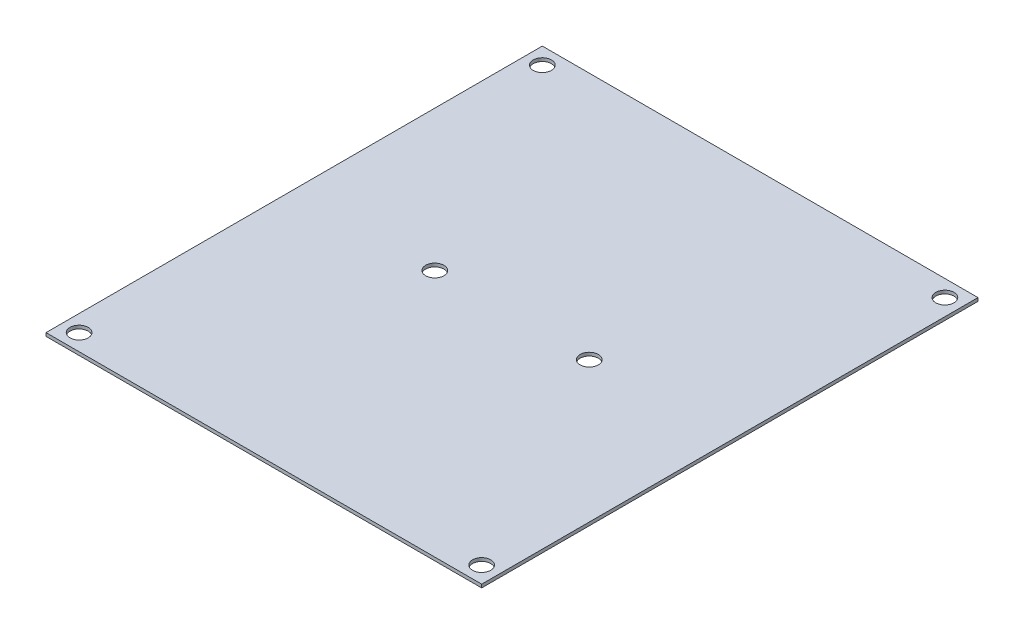
SolidWorks part; units mm, degrees
ref_plane "Front Plane" through (0, 0, 0) normal (0, 0, 1) x (1, 0, 0)
ref_plane "Top Plane" through (0, 0, 0) normal (0, 1, 0) x (1, 0, 0)
ref_plane "Right Plane" through (0, 0, 0) normal (1, 0, 0) x (0, 0, -1)
sketch "Sketch1" plane through (0, 0, 0) normal (0, 1, 0) x (1, 0, 0)
  line L1 (0, 0) -> (79, 0)
  line L2 (0, 0) -> (0, 90)
  line L3 (0, 90) -> (79, 90)
  line L4 (79, 0) -> (79, 90)
  dimension "D1" = 90
  dimension "D2" = 79
extrude "Boss-Extrude1" add sketch "Sketch1" along normal blind 0.6
sketch "Sketch2" plane through (0, 0.6, 0) normal (0, 1, 0) x (1, 0, 0)
  line L0 (39.5, 90) -> (39.5, 0) construction
  line L1 (79, 90) -> (0, 90) construction
  line L2 (0, 0) -> (79, 0) construction
  line L4 (53.5, 45) -> (25.5, 45) construction
  line L5 (76, 3) -> (3, 3) construction
  line L6 (76, 3) -> (76, 87) construction
  line L7 (76, 87) -> (3, 87) construction
  line L8 (3, 3) -> (3, 87) construction
  line L9 (76, 3) -> (3, 87) construction
  line L10 (76, 87) -> (3, 3) construction
  circle A0 centre (3, 87) radius 1.65
  circle A1 centre (76, 87) radius 1.65
  circle A2 centre (53.5, 45) radius 1.65
  circle A3 centre (25.5, 45) radius 1.65
  circle A4 centre (76, 3) radius 1.65
  circle A5 centre (3, 3) radius 1.65
  point P6 (39.5, 45)
  point P8 (39.5, 45)
  point P12 (39.5, 45)
  dimension "D4" = 3.3
  dimension "D1" = 28
  dimension "D2" = 73
  dimension "D3" = 84
extrude "Cut-Extrude1" cut sketch "Sketch2" against normal through all
ref_plane "Plane1" through (0, 0, -45) normal (0, 0, -1) x (-1, 0, 0)
ref_plane "Plane2" through (39.5, 0, 0) normal (1, 0, 0) x (0, 0, -1)
